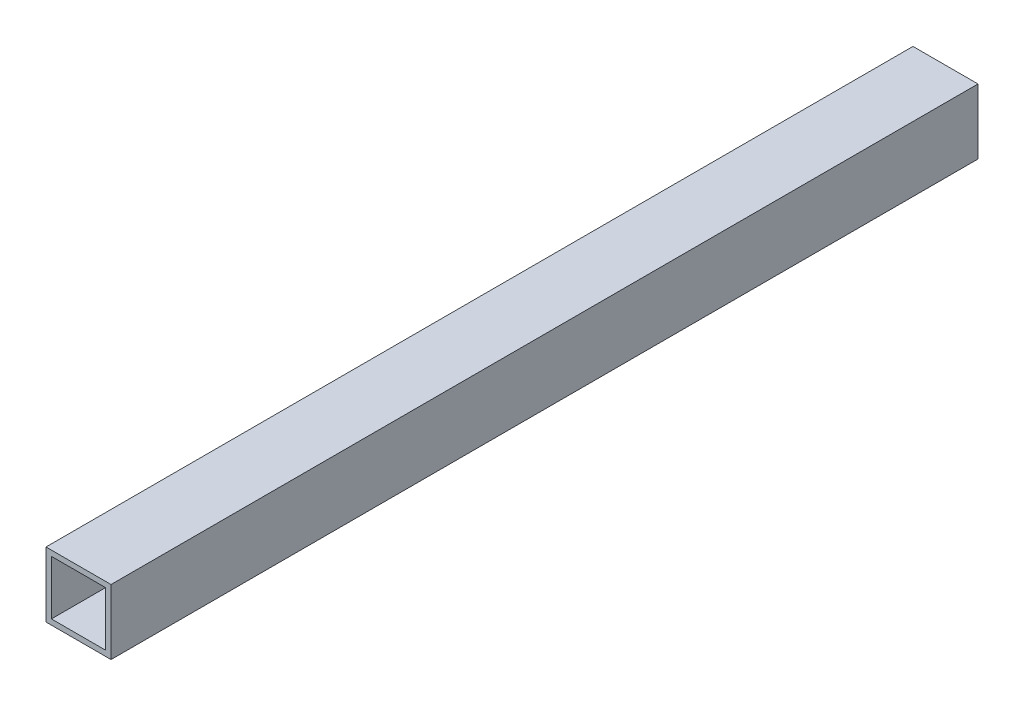
SolidWorks part; units mm, degrees
ref_plane "Front Plane" through (0, 0, 0) normal (0, 0, 1) x (1, 0, 0)
ref_plane "Top Plane" through (0, 0, 0) normal (0, 1, 0) x (1, 0, 0)
ref_plane "Right Plane" through (0, 0, 0) normal (1, 0, 0) x (0, 0, -1)
sketch "Sketch1" plane through (0, 0, 0) normal (0, 0, 1) x (1, 0, 0)
  line L0 (19.05, 0) -> (15.875, 0) construction
  line L1 (-19.05, 0) -> (19.05, 0) construction
  line L2 (0, 19.05) -> (0, -19.05)
  point P7 (0, 0)
sketch "Sketch2" plane through (0, 0, 0) normal (1, 0, 0) x (0, 0, -1)
  line L0 (254, 0) -> (-254, 0)
  point P4 (0, 0)
  dimension "Length" = 508
sketch "Sketch3" plane through (0, 0, 0) normal (0, 0, 1) x (1, 0, 0)
  line L0 (-19.05, 0) -> (19.05, 0) construction
  line L5 (19.05, -19.05) -> (-19.05, -19.05)
  line L6 (19.05, -19.05) -> (19.05, 19.05)
  line L11 (19.05, 19.05) -> (-19.05, 19.05)
  line L12 (-19.05, -19.05) -> (-19.05, 19.05)
  line L14 (19.05, -19.05) -> (-19.05, 19.05) construction
  line L15 (19.05, 19.05) -> (-19.05, -19.05) construction
  line L16 (15.875, -15.875) -> (-15.875, -15.875)
  line L17 (15.875, -15.875) -> (15.875, 15.875)
  line L18 (15.875, 15.875) -> (-15.875, 15.875)
  line L19 (-15.875, -15.875) -> (-15.875, 15.875)
  line L20 (15.875, -15.875) -> (-15.875, 15.875) construction
  line L21 (15.875, 15.875) -> (-15.875, -15.875) construction
  point P0 (0, 0)
  point P5 (0, 0)
  point P13 (15.875, -19.05)
  dimension "D1" = 3.175
  dimension "D3" = 38.1
  dimension "D4" = 38.1
  dimension "D2" = 3.175
extrude "Boss-Extrude1" add sketch "Sketch3" along normal up to vertex (254 mm away) and the other way up to vertex (254 mm away) up to point (0, 0, 254) other way up to point (0, 0, -254)
sketch "Sketch5" plane through (0, 0, 0) normal (1, 0, 0) x (0, 0, -1)
  line L0 (-254, 0) -> (254, 0) construction
  line L3 (-254, -19.05) -> (-254, 19.05) construction
  line L4 (254, -19.05) -> (254, 19.05) construction
  point P6 (-211.1375, 0)
  point P7 (-196.85, 0)
  point P8 (196.85, 0)
  point P10 (211.1375, 0)
  dimension "D1" = 42.8625
  dimension "D2" = 57.15
  dimension "D3" = 42.8625
  dimension "D4" = 57.15
equation "\"D1@Sketch3\"=\"Wall thickness@Sketch1\""
equation "\"D1@Sketch5\"=\"Width@Sketch1\"*1.125"
equation "\"D2@Sketch5\"=\"Width@Sketch1\"*1.5"
equation "\"D3@Sketch5\"=\"D1@Sketch5\""
equation "\"D4@Sketch5\"=\"D2@Sketch5\""
equation "\"D2@Sketch3\"=\"Wall Thickness@Sketch1\""
